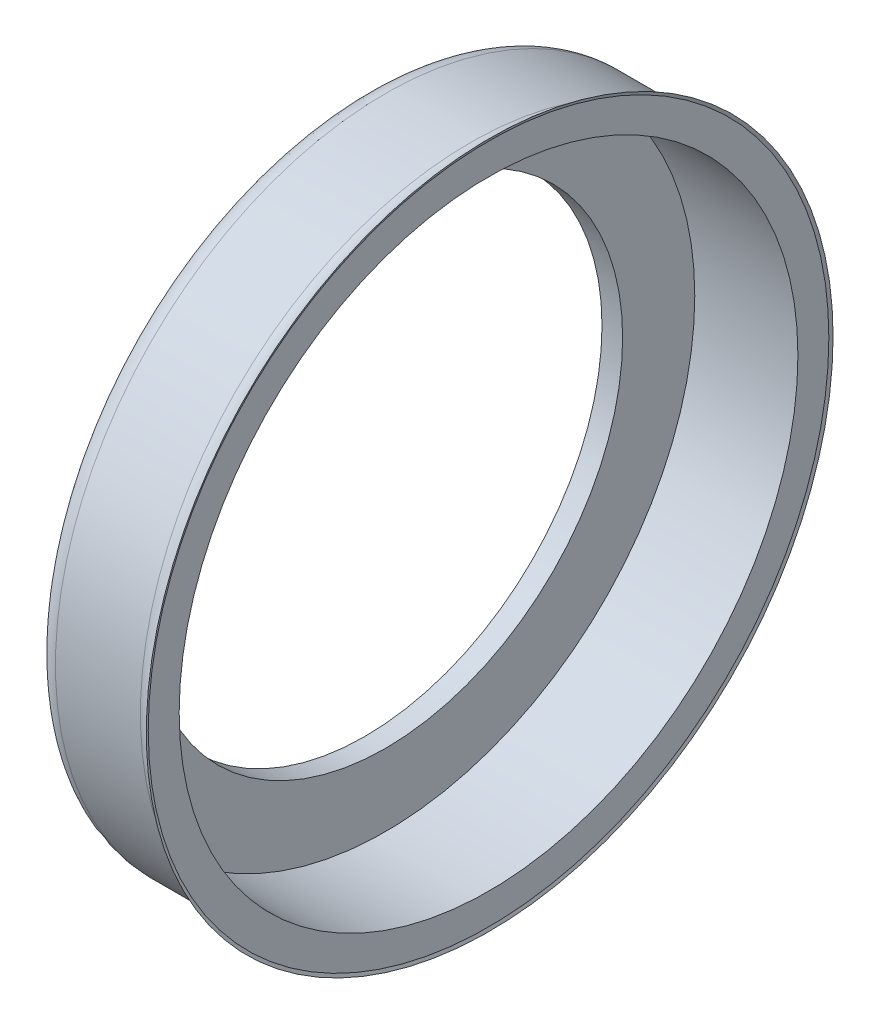
SolidWorks part; units mm, degrees
ref_plane "Alzado" through (0, 0, 0) normal (0, 0, 1) x (1, 0, 0)
ref_plane "Planta" through (0, 0, 0) normal (0, 1, 0) x (1, 0, 0)
ref_plane "Vista lateral" through (0, 0, 0) normal (1, 0, 0) x (0, 0, -1)
sketch "Croquis1" plane through (0, 0, 0) normal (0, 1, 0) x (1, 0, 0)
  line L0 (0, 0) -> (0, 15) construction
  line L8 (-0.8805, 16) -> (-5, 16)
  line L9 (-6, 15) -> (-6, 11.5015)
  line L10 (-6, 11.5015) -> (-5, 11.5015)
  line L11 (-5, 11.5015) -> (-5, 15)
  line L12 (-5, 15) -> (0, 15)
  line L13 (0, 15) -> (0, 16.5)
  line L14 (0, 16.5) -> (0.0559, 16.6491)
  line L15 (0, 0) -> (-5.5, 0) construction
  arc A2 (-5, 16) -> (-6, 15) centre (-5, 15) ccw
  arc A3 (0.0559, 16.6491) -> (-0.8805, 16) centre (-0.8805, 17) cw
  dimension "D2" = 3.4985
  dimension "D5" = 1
  dimension "D1" = 15
  dimension "D3" = 1
  dimension "D4" = 1
  dimension "D6" = 1.5
  dimension "D7" = 5
revolve "Revolución1" add sketch "Croquis1" angle 360 about L15
